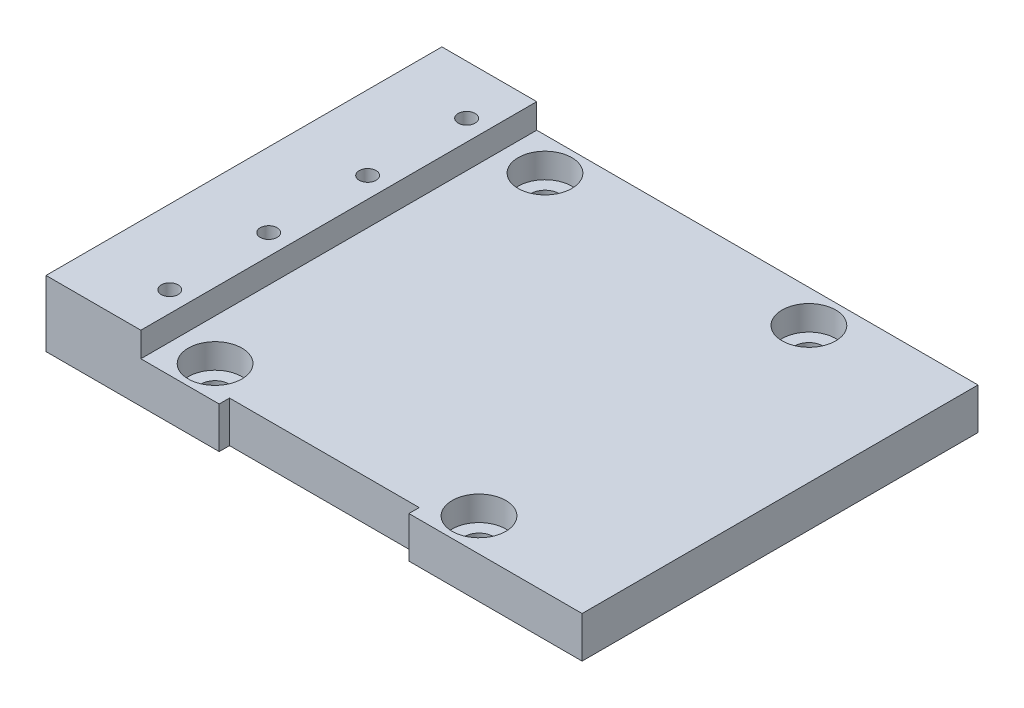
SolidWorks part; units mm, degrees
ref_plane "Front Plane" through (0, 0, 0) normal (0, 0, 1) x (1, 0, 0)
ref_plane "Top Plane" through (0, 0, 0) normal (0, 1, 0) x (1, 0, 0)
ref_plane "Right Plane" through (0, 0, 0) normal (1, 0, 0) x (0, 0, -1)
sketch "Sketch1" plane through (0, 0, 0) normal (0, 1, 0) x (1, 0, 0)
  line L1 (-32.5, 24) -> (32.5, 24)
  line L2 (-32.5, 24) -> (-32.5, -24)
  line L3 (-32.5, -24) -> (32.5, -24)
  line L4 (32.5, 24) -> (32.5, -24)
  line L5 (-32.5, 24) -> (32.5, -24) construction
  line L6 (-32.5, -24) -> (32.5, 24) construction
  point P0 (0, 0)
  dimension "D1" = 48
  dimension "D2" = 65
extrude "Boss-Extrude1" add sketch "Sketch1" along normal blind 5
sketch "Sketch2" plane through (0, 5, 0) normal (0, 1, 0) x (1, 0, 0)
  line L0 (-32.5, -24) -> (32.5, -24) construction
  line L1 (-32.5, 24) -> (-21, 24)
  line L2 (-32.5, 24) -> (-32.5, -24)
  line L3 (-32.5, -24) -> (-21, -24)
  line L4 (-21, 24) -> (-21, -24)
  dimension "D1" = 11.5
extrude "Boss-Extrude2" add sketch "Sketch2" along normal blind 3
hole_wizard "M2.5x0.45 Tapped Hole1" positions "Sketch3" profile "Sketch4" tap size "M2.5x0.45" standard "ANSI Metric"
sketch "Sketch3" plane through (0, 8, 0) normal (0, 1, 0) x (1, 0, 0)
  line L0 (-32.5, 24) -> (-32.5, -24) construction
  line L1 (-32.5, -24) -> (-21, -24) construction
  point P0 (-23.5, 18)
  point P2 (-23.5, 6)
  point P4 (-23.5, -18)
  point P6 (-23.5, -6)
  dimension "D1" = 9
  dimension "D2" = 42
  dimension "D3" = 30
  dimension "D4" = 18
  dimension "D5" = 6
sketch "Sketch4" plane through (-23.5, 8, -18) normal (1, 0, 0) x (0, 0, 1)
  line L0 (0, 0) -> (0, 6.35)
  line L1 (0, 6.35) -> (1.025, 6.35)
  line L2 (1.025, 6.35) -> (1.025, 0)
  line L5 (1.025, 0) -> (0, 0)
  line L10 (0, 6.35) -> (-1.025, 6.35) construction
  line L11 (0, -6.35) -> (0, 107.95) construction
  dimension "Tap Drill Dia." = 2.05
  dimension "Tap Drill Depth" = 6.35
  dimension "Drill Angle" = 180
cosmetic thread "Hole Thread1" parameters "D1"=5, "D2"=2.5
cosmetic thread "Hole Thread2" parameters "D1"=5, "D2"=2.5
cosmetic thread "Hole Thread3" parameters "D1"=5, "D2"=2.5
cosmetic thread "Hole Thread4" parameters "D1"=5, "D2"=2.5
hole_wizard "CBORE for M3 SHCS1" positions "Sketch5" profile "Sketch6" counterbore size "M3" standard "ANSI Metric" end condition through all
sketch "Sketch5" plane through (0, 5, 0) normal (0, 1, 0) x (1, 0, 0)
  line L0 (-32.5, 24) -> (-32.5, -24) construction
  line L1 (-21, -24) -> (32.5, -24) construction
  point P0 (-16, 20)
  point P2 (16, 20)
  point P4 (-16, -20)
  point P6 (16, -20)
  dimension "D1" = 16.5
  dimension "D2" = 48.5
  dimension "D3" = 4
  dimension "D4" = 44
sketch "Sketch6" plane through (-16, 5, -20) normal (1, 0, 0) x (0, 0, 1)
  line L0 (0, 0) -> (0, 5)
  line L1 (0, 5) -> (1.7, 5)
  line L3 (1.7, 5) -> (1.7, 3)
  line L4 (1.7, 3) -> (3.25, 3)
  line L5 (3.25, 3) -> (3.25, 0)
  line L7 (3.25, 0) -> (0, 0)
  line L11 (0, -6.35) -> (0, 107.95) construction
  dimension "Thru Hole Dia." = 3.4
  dimension "Thru Hole Depth" = 5
  dimension "C'Bore Dia." = 6.5
  dimension "C'Bore Depth" = 3
sketch "Sketch7" plane through (0, 0, 24) normal (0, 0, 1) x (1, 0, 0)
  line L5 (-21, 5) -> (32.5, 5) construction
  line L6 (-11.5, 5) -> (11.5, 5)
  line L7 (-11.5, 5) -> (-11.5, 0)
  line L8 (-11.5, 0) -> (11.5, 0)
  line L9 (11.5, 5) -> (11.5, 0)
  line L10 (-32.5, 0) -> (32.5, 0) construction
  line L11 (-32.5, 8) -> (-32.5, 0) construction
  dimension "D1" = 21
  dimension "D2" = 44
extrude "Cut-Extrude1" cut sketch "Sketch7" against normal blind 1.25
